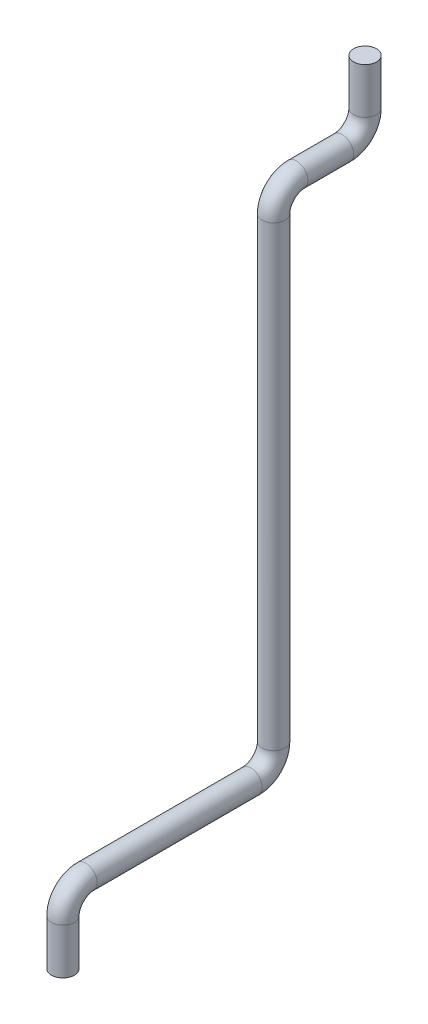
SolidWorks part; units mm, degrees
material "Acrilico TEC"
ref_plane "Front Plane" through (0, 0, 0) normal (0, 0, 1) x (1, 0, 0)
ref_plane "Top Plane" through (0, 0, 0) normal (0, 1, 0) x (1, 0, 0)
ref_plane "Right Plane" through (0, 0, 0) normal (1, 0, 0) x (0, 0, -1)
sketch "Sketch1" plane through (0, 0, 0) normal (1, 0, 0) x (0, 0, -1)
  line L0 (0, 0) -> (0, 2)
  line L1 (1, 3) -> (8.22, 3)
  line L2 (9.22, 4) -> (9.22, 24)
  line L3 (10.22, 25) -> (12.22, 25)
  line L4 (13.22, 26) -> (13.22, 28)
  arc A1 (0, 2) -> (1, 3) centre (1, 2) cw
  arc A2 (8.22, 3) -> (9.22, 4) centre (8.22, 4) ccw
  arc A3 (9.22, 24) -> (10.22, 25) centre (10.22, 24) cw
  arc A4 (12.22, 25) -> (13.22, 26) centre (12.22, 26) ccw
  point P13 (0, 3)
  point P16 (9.22, 3)
  point P19 (9.22, 25)
  point P22 (13.22, 25)
  dimension "D6" = 1
  dimension "D7" = 1
  dimension "D8" = 1
  dimension "D9" = 1
  dimension "D1" = 3
  dimension "D2" = 4
  dimension "D3" = 22
  dimension "D4" = 9.22
  dimension "D5" = 3
ref_plane "Plane1" through (0, 0, 0) normal (0, 1, 0) x (1, 0, 0)
sketch "Sketch2" plane through (0, 0, 0) normal (0, 1, 0) x (1, 0, 0)
  circle A0 centre (0, 0) radius 0.5
  dimension "D1" = 1
sweep "Sweep1" add profiles "Sketch2" path "Sketch1"
